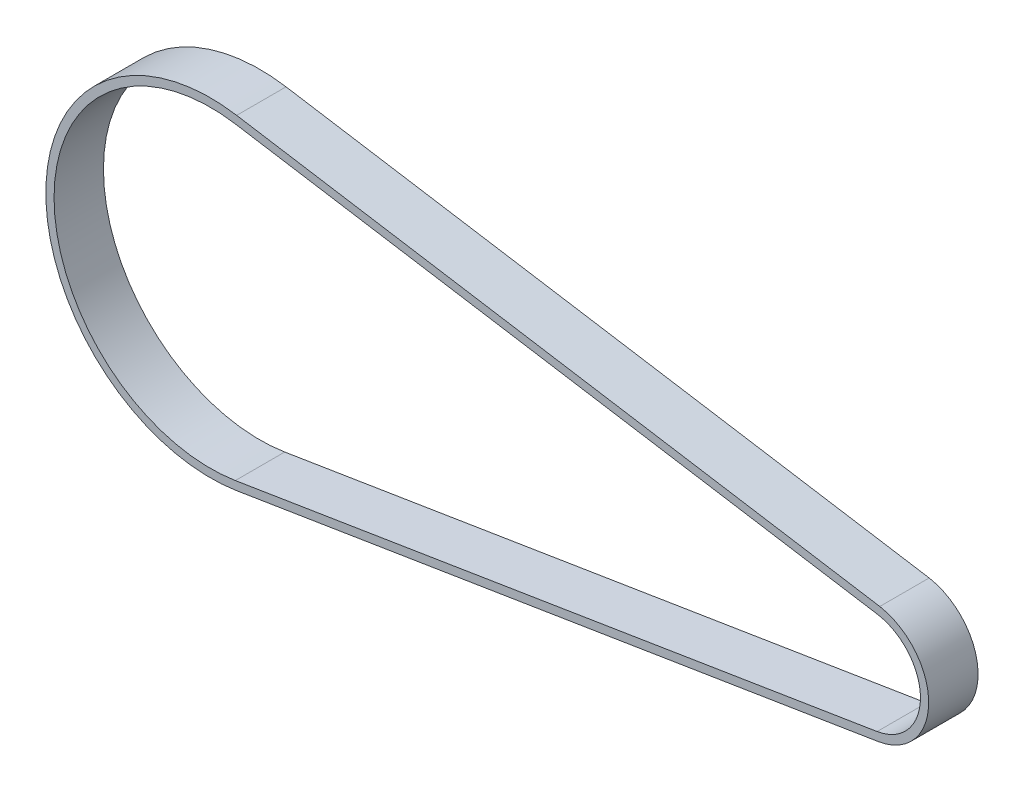
SolidWorks part; units mm, degrees
ref_plane "Přední rovina" through (0, 0, 0) normal (0, 0, 1) x (1, 0, 0)
ref_plane "Horní rovina" through (0, 0, 0) normal (0, 1, 0) x (1, 0, 0)
ref_plane "Pravá rovina" through (0, 0, 0) normal (1, 0, 0) x (0, 0, -1)
sketch "Skica1" plane through (0, 0, 0) normal (0, 0, 1) x (1, 0, 0)
  line L0 (0, 0) -> (80, 0) construction
  line L2 (3.0257, -18.7575) -> (80.9969, -6.1801)
  line L5 (3.185, -19.7448) -> (81.1562, -7.1673)
  line L6 (3.1855, 19.7447) -> (81.3196, 7.1391)
  line L8 (3.0258, 18.7575) -> (80.9969, 6.1801)
  arc A0 (3.0258, 18.7575) -> (3.0257, -18.7575) centre (0, 0) ccw
  arc A1 (80.9969, -6.1801) -> (80.9969, 6.1801) centre (80, 0) ccw
  circle A4 centre (80, 0) radius 6.26 construction
  circle A5 centre (0, 0) radius 19 construction
  arc A7 (3.1855, 19.7447) -> (3.185, -19.7448) centre (0, 0) ccw
  arc A13 (81.1562, -7.1673) -> (81.3196, 7.1391) centre (80, 0) ccw
  arc A16 (26.4645, 11.1989) -> (80.9383, 6.1893) centre (73.3043, 221.8542) ccw construction
  arc A17 (26.4645, 11.1989) -> (7.691, 17.3738) centre (48.1697, 108.8149) cw construction
  arc A18 (26.6816, 12.175) -> (8.0958, 18.2882) centre (48.1697, 108.8149) cw construction
  arc A19 (26.6816, 12.175) -> (80.9924, 7.1918) centre (73.3043, 221.8542) ccw construction
  arc A21 (81.1562, -7.1673) -> (80.9924, 7.1918) centre (80, 0) ccw construction
  arc A22 (8.0958, 18.2882) -> (3.185, -19.7448) centre (0, 0) ccw construction
  arc A23 (7.691, 17.3738) -> (3.0257, -18.7575) centre (0, 0) ccw construction
  arc A24 (80.9969, -6.1801) -> (80.9383, 6.1893) centre (80, 0) ccw construction
  point P1 (0, 0)
  point P4 (11.8135, 16.1382)
  point P6 (2.9976, -19.7741)
  dimension "D1" = 80
  dimension "D2" = 38
  dimension "D3" = 12.52
  dimension "D4" = 1
extrude "Přidat vysunutím1" add sketch "Skica1" along normal blind 6
